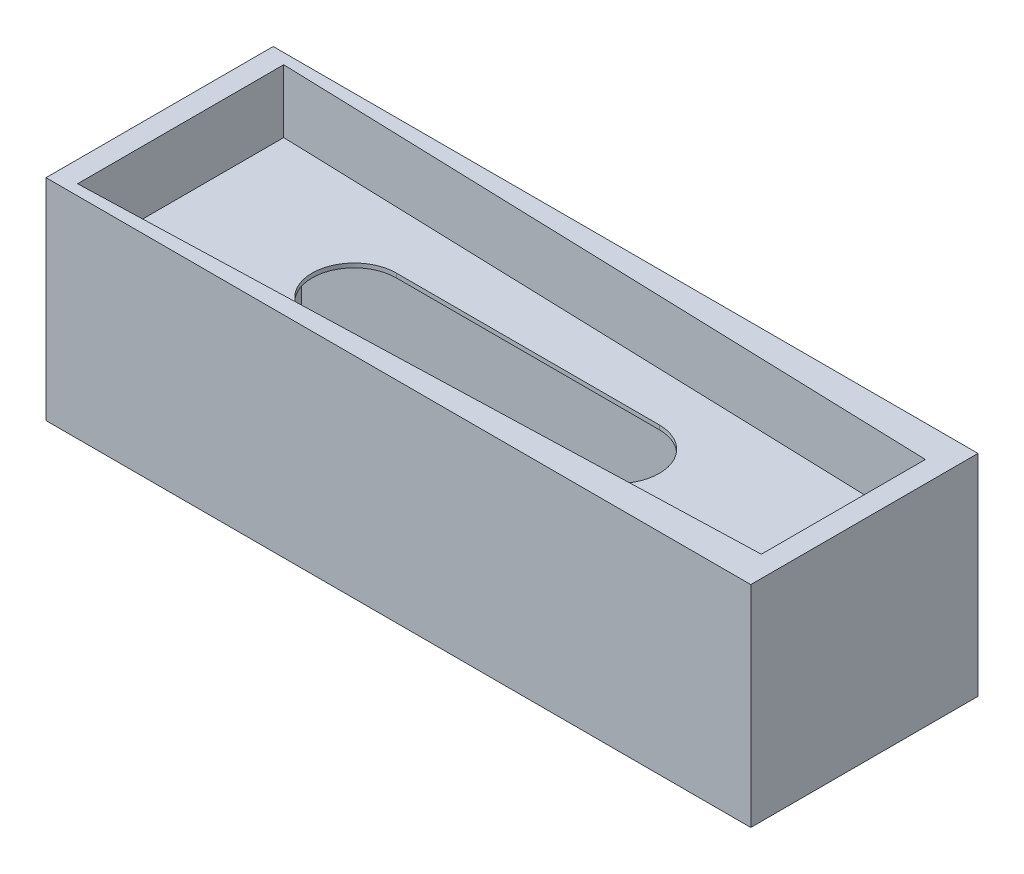
SolidWorks part; units mm, degrees
ref_plane "Front Plane" through (0, 0, 0) normal (0, 0, 1) x (1, 0, 0)
ref_plane "Top Plane" through (0, 0, 0) normal (0, 1, 0) x (1, 0, 0)
ref_plane "Right Plane" through (0, 0, 0) normal (1, 0, 0) x (0, 0, -1)
sketch "Sketch2" plane through (0, 0, 0) normal (0, 1, 0) x (1, 0, 0)
  line L1 (-167.5, 54) -> (167.5, 54)
  line L2 (-167.5, 54) -> (-167.5, -54)
  line L3 (-167.5, -54) -> (167.5, -54)
  line L4 (167.5, 54) -> (167.5, -54)
  line L5 (-167.5, 54) -> (167.5, -54) construction
  line L6 (-167.5, -54) -> (167.5, 54) construction
  point P0 (0, 0)
  dimension "D1" = 335
  dimension "D2" = 108
extrude "Boss-Extrude4" add sketch "Sketch2" against normal blind 100
sketch "Sketch3" plane through (0, 0, 0) normal (0, 1, 0) x (1, 0, 0)
  line L0 (-157.5, -49) -> (-157.5, 49)
  line L1 (157.5, -39) -> (157.5, 39)
  line L2 (-175, 0) -> (175, 0) construction
  line L3 (-157.5, 49) -> (157.5, 39)
  line L4 (157.5, -39) -> (-157.5, -49)
  line L5 (-167.5, 54) -> (-167.5, -54) construction
  line L6 (167.5, -54) -> (167.5, 54) construction
  point P3 (-157.5, 0)
  point P9 (157.5, 0)
  dimension "D1" = 98
  dimension "D2" = 78
  dimension "D3" = 10
  dimension "D4" = 10
  dimension "D5" = 315
extrude "Cut-Extrude1" cut sketch "Sketch3" against normal blind 30 contours L3 L1 L4 L0
sketch "Sketch4" plane through (0, -100, 0) normal (0, -1, 0) x (-1, 0, 0)
  line L1 (150, -50) -> (-150, -50)
  line L2 (150, -50) -> (150, 50)
  line L3 (150, 50) -> (-150, 50)
  line L4 (-150, -50) -> (-150, 50)
  dimension "D1" = 300
  dimension "D2" = 100
extrude "Cut-Extrude2" cut sketch "Sketch4" against normal blind 68 contours L2 L3 L4 L1
sketch "Sketch5" plane through (0, -30, 0) normal (0, 1, 0) x (1, 0, 0)
  line L0 (-75, 0) -> (50, 0) construction
  line L1 (-75, 20) -> (50, 20)
  line L2 (-75, -20) -> (50, -20)
  arc A0 (-75, 20) -> (-75, -20) centre (-75, 0) ccw
  arc A1 (50, -20) -> (50, 20) centre (50, 0) ccw
  point P3 (-12.5, 0)
  dimension "D1" = 20
  dimension "D2" = 125
extrude "Cut-Extrude3" cut sketch "Sketch5" against normal blind 31
